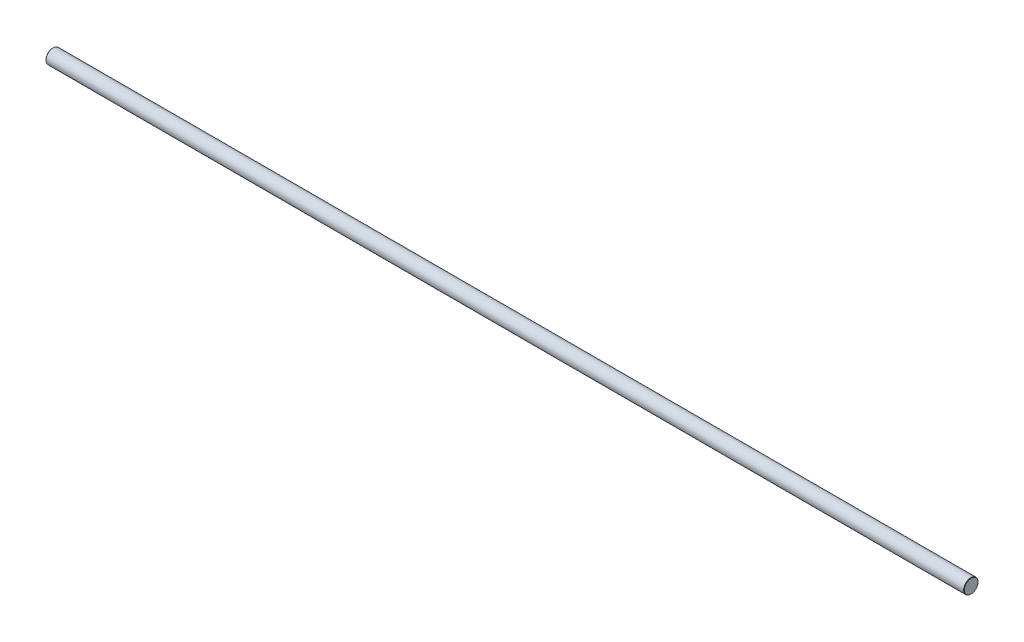
SolidWorks part; units mm, degrees
ref_plane "Front Plane" through (0, 0, 0) normal (0, 0, 1) x (1, 0, 0)
ref_plane "Top Plane" through (0, 0, 0) normal (0, 1, 0) x (1, 0, 0)
ref_plane "Right Plane" through (0, 0, 0) normal (1, 0, 0) x (0, 0, -1)
sketch "Sketch1" plane through (0, 0, 0) normal (1, 0, 0) x (0, 0, -1)
  circle A0 centre (0, 0) radius 4.7625 construction
  circle A2 centre (0, 0) radius 4.7879 construction
  dimension "Diameter" = 9.525
  dimension "Finish Thickness" = 0.0254
sketch "Sketch2" plane through (0, 0, 0) normal (0, 0, 1) x (1, 0, 0)
  line L0 (0, 0) -> (304.8, 0) construction
  line L1 (0, 0) -> (-304.8, 0) construction
  line L2 (304.8, 0) -> (304.8, 4.7625) construction
  line L3 (304.8, 0) -> (304.8, -4.7625) construction
  line L4 (304.8, 4.7625) -> (0, 4.7625) construction
  line L7 (0, 4.7625) -> (-304.8, 4.7625) construction
  line L8 (-304.8, 4.7625) -> (-304.8, 0) construction
  point P5 (-254, 0)
  point P8 (254, 0)
  dimension "Length" = 609.6
  dimension "D1" = 50.8
  dimension "D2" = 50.8
sketch "Sketch4" plane through (0, 0, 0) normal (1, 0, 0) x (0, 0, -1)
  circle A0 centre (0, 0) radius 4.7625 construction
  circle A1 centre (0, 0) radius 4.7625
extrude "Boss-Extrude1" add sketch "Sketch4" along normal up to vertex (304.8 mm away) and the other way up to vertex (304.8 mm away) up to point (304.8, 0, 0) other way up to point (-304.8, 0, 0)
chamfer "Chamfer1" distance 0.2476 angle 45 2 edges at (-304.8, 0, -4.7625) (304.8, 0, -4.7625)
equation "\"D1@Chamfer1\" = \"Diameter@Sketch1\" * .026"
equation "\"D2@Sketch2\" = \"D1@Sketch2\""
